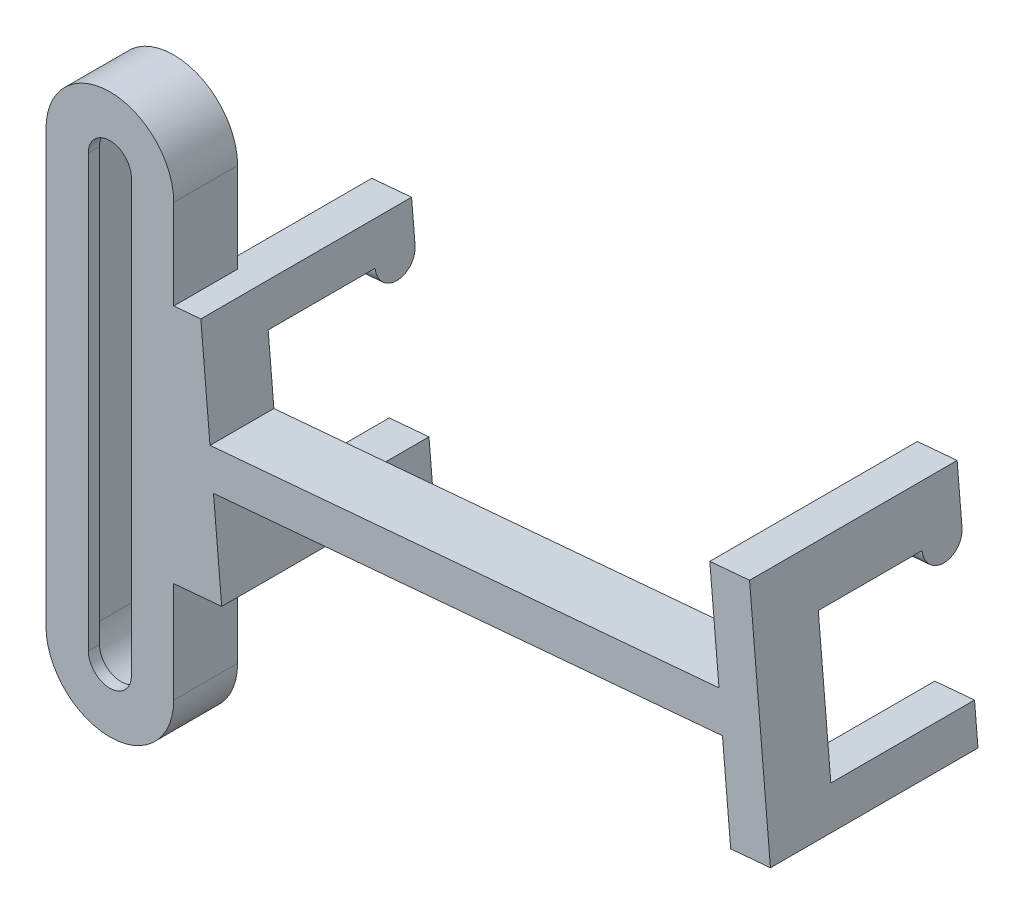
SolidWorks part; units mm, degrees
ref_plane "Front Plane" through (0, 0, 0) normal (0, 0, 1) x (1, 0, 0)
ref_plane "Top Plane" through (0, 0, 0) normal (0, 1, 0) x (1, 0, 0)
ref_plane "Right Plane" through (0, 0, 0) normal (1, 0, 0) x (0, 0, -1)
sketch "Sketch1" plane through (0, 0, 0) normal (0, 0, 1) x (1, 0, 0)
  line L1 (-10.16, -34.29) -> (10.16, -34.29)
  line L2 (-10.16, -34.29) -> (-10.16, 34.29)
  line L3 (-10.16, 34.29) -> (10.16, 34.29)
  line L4 (10.16, -34.29) -> (10.16, 34.29)
  line L5 (-10.16, -34.29) -> (10.16, 34.29) construction
  line L6 (-10.16, 34.29) -> (10.16, -34.29) construction
  circle A0 centre (0, 34.29) radius 10.16
  circle A1 centre (0, -34.29) radius 10.16
  point P0 (0, 0)
  dimension "D1" = 20.32
  dimension "D2" = 68.58
extrude "Boss-Extrude1" add sketch "Sketch1" along normal blind 10.16 contours A0 | L2 L1 L4 L3 | A1
sketch "Sketch2" plane through (0, 0, 10.16) normal (0, 0, 1) x (1, 0, 0)
  line L0 (6.604, 0) -> (10.16, 0) construction
  line L1 (-6.604, -34.29) -> (6.604, -34.29)
  line L2 (-6.604, -34.29) -> (-6.604, 34.29)
  line L3 (-6.604, 34.29) -> (6.604, 34.29)
  line L4 (6.604, -34.29) -> (6.604, 34.29)
  line L5 (-6.604, -34.29) -> (6.604, 34.29) construction
  line L6 (-6.604, 34.29) -> (6.604, -34.29) construction
  line L7 (10.16, -34.29) -> (10.16, 34.29) construction
  line L8 (0, 40.894) -> (0, 44.45) construction
  circle A0 centre (0, 34.29) radius 6.604
  circle A1 centre (0, -34.29) radius 6.604
  arc A2 (10.16, 34.29) -> (-10.16, 34.29) centre (0, 34.29) ccw construction
  point P0 (0, 0)
  dimension "D1" = 13.208
extrude "Cut-Extrude1" cut sketch "Sketch2" against normal through all contours A0 | L2 L1 L4 L3 | A1
sketch "Sketch3" plane through (0, 0, 0) normal (0, 0, -1) x (-1, 0, 0)
  line L0 (-10.16, -34.29) -> (-10.16, 34.29) construction
  line L1 (-9.6066, 3.1387) -> (-103.2289, 11.3296)
  line L2 (-9.6066, 3.1387) -> (-10.16, -3.1871)
  line L3 (-10.16, -3.1871) -> (-103.7824, 5.0038)
  line L4 (-103.2289, 11.3296) -> (-103.7824, 5.0038)
  line L5 (-103.5057, 8.1667) -> (-10.16, 0) construction
  dimension "D1" = 6.35
  dimension "D2" = 93.98
  dimension "D3" = 85
extrude "Boss-Extrude2" add sketch "Sketch3" against normal up to surface (10.16 mm away) up to face at (0, 0, 10.16)
ref_plane "Plane1" through (9.8061, 0.8579, 0) normal (-0.9962, -0.0872, 0) x (0, 0, 1)
sketch "Sketch4" plane through (-103.0822, 1291.1777, 0) normal (-0.9962, -0.0872, 0) x (0, 0, -1)
  line L1 (23.368, 1276.1986) -> (-10.16, 1276.1986)
  line L2 (23.368, 1276.1986) -> (23.368, 1314.2986)
  line L3 (23.368, 1314.2986) -> (-10.16, 1314.2986)
  line L4 (-10.16, 1276.1986) -> (-10.16, 1314.2986)
  line L5 (23.368, 1276.1986) -> (-10.16, 1314.2986) construction
  line L6 (23.368, 1314.2986) -> (-10.16, 1276.1986) construction
  line L7 (-10.16, 1292.9591) -> (-10.16, 1261.9746) construction
  line L8 (-10.16, 1328.5226) -> (-10.16, 1260.2036) construction
  point P0 (6.604, 1295.2486)
  dimension "D1" = 33.528
  dimension "D2" = 38.1
extrude "Boss-Extrude3" add sketch "Sketch4" against normal blind 6.35
sketch "Sketch5" plane through (16.1319, 1.4114, 0) normal (0.9962, 0.0872, 0) x (0, 0, 1)
  line L1 (-23.368, -12.7) -> (0, -12.7)
  line L2 (-23.368, -12.7) -> (-23.368, 12.7)
  line L3 (-23.368, 12.7) -> (0, 12.7)
  line L4 (0, -12.7) -> (0, 12.7)
  line L5 (-23.368, -12.7) -> (0, 12.7) construction
  line L6 (-23.368, 12.7) -> (0, -12.7) construction
  line L7 (0, 35.045) -> (0, 4.0605) construction
  line L8 (-23.368, -19.05) -> (-23.368, 19.05) construction
  point P0 (-11.684, 0)
  dimension "D2" = 25.4
extrude "Cut-Extrude2" cut sketch "Sketch5" against normal through all contours L3 L4 L1 L2
sketch "Sketch6" plane through (103.4285, 9.0488, 0) normal (0.9962, 0.0872, 0) x (0, 0, -1)
  line L8 (23.368, -19.05) -> (-10.16, -19.05) construction
  line L11 (-10.16, 19.05) -> (22.86, 19.05)
  line L13 (-10.16, 19.05) -> (-10.16, -19.05)
  line L14 (-10.16, -19.05) -> (22.86, -19.05)
  line L15 (22.86, 19.05) -> (22.86, -19.05)
  line L16 (0, 12.7) -> (0, 2.2895) construction
  dimension "D1" = 22.86
extrude "Boss-Extrude4" add sketch "Sketch6" against normal blind 6.35
sketch "Sketch7" plane through (9.8061, 0.8579, 0) normal (-0.9962, -0.0872, 0) x (0, 0, 1)
  line L0 (0, -4.0605) -> (0, -19.05)
  line L1 (0, -33.274) -> (0, 35.045) construction
  line L2 (-23.368, -19.05) -> (10.16, -19.05) construction
  line L3 (0, -19.05) -> (10.16, -19.05)
  line L4 (10.16, -33.274) -> (10.16, 35.045) construction
  line L5 (10.16, -19.05) -> (10.16, -4.0605)
  line L6 (10.16, -4.0605) -> (0, -4.0605)
extrude "Boss-Extrude5" add sketch "Sketch7" along normal up to next
sketch "Sketch8" plane through (97.1026, 8.4954, 0) normal (-0.9962, -0.0872, 0) x (0, 0, 1)
  line L0 (0, -33.274) -> (0, 35.045) construction
  line L1 (0, 10.16) -> (-22.86, 10.16)
  line L2 (0, 10.16) -> (0, -12.7)
  line L3 (0, -12.7) -> (-22.86, -12.7)
  line L4 (-22.86, 10.16) -> (-22.86, -12.7)
  line L5 (-22.86, -19.05) -> (-22.86, 19.05) construction
  line L7 (0, -12.7) -> (-23.368, -12.7) construction
  dimension "D1" = 22.86
extrude "Cut-Extrude3" cut sketch "Sketch8" against normal through all
sketch "Sketch9" plane through (9.8061, 0.8579, 0) normal (-0.9962, -0.0872, 0) x (0, 0, 1)
  line L1 (0, 12.7) -> (-23.368, 12.7) construction
  line L2 (-23.368, 19.05) -> (-23.368, 12.7) construction
  circle A0 centre (-20.193, 12.7) radius 3.175
  dimension "D1" = 6.35
extrude "Boss-Extrude6" add sketch "Sketch9" against normal up to surface (6.35 mm away) up to face at (17.1723, -10.48, -4.4027)
sketch "Sketch10" plane through (97.1026, 8.4954, 0) normal (-0.9962, -0.0872, 0) x (0, 0, 1)
  line L1 (0, 10.16) -> (-22.86, 10.16) construction
  line L2 (-22.86, 10.16) -> (-22.86, 19.05) construction
  circle A0 centre (-19.685, 10.16) radius 3.175
  dimension "D1" = 6.35
extrude "Boss-Extrude7" add sketch "Sketch10" against normal up to surface (6.35 mm away) up to face at (103.4838, 8.4162, -8.89)
sketch "Sketch13" plane through (16.1319, 1.4114, 0) normal (0.9962, 0.0872, 0) x (0, 0, -1)
  line L0 (-10.16, -4.0605) -> (0, -4.0605) construction
  circle A0 centre (-5.08, -4.0605) radius 2.286
  dimension "D1" = 4.572
extrude "Cut-Extrude4" cut sketch "Sketch13" against normal up to surface (81.28 mm away)
sketch "Sketch14" plane through (0, 0, 10.16) normal (0, 0, 1) x (1, 0, 0)
  line L0 (-3.429, 0) -> (3.429, 0) construction
  line L1 (0, 37.719) -> (0, 40.894) construction
  line L2 (3.429, 0) -> (6.604, 0) construction
  line L4 (-3.429, -34.29) -> (-3.429, 34.29)
  line L6 (3.429, -34.29) -> (3.429, 34.29)
  line L7 (6.604, -34.29) -> (6.604, 34.29) construction
  line L8 (-10.16, -34.29) -> (-10.16, 34.29) construction
  line L9 (-10.16, -34.29) -> (-10.16, 34.29)
  line L10 (10.16, 34.29) -> (10.16, -34.29)
  arc A0 (6.604, 34.29) -> (-6.604, 34.29) centre (0, 34.29) ccw construction
  arc A1 (3.429, 34.29) -> (-3.429, 34.29) centre (0, 34.29) ccw
  arc A2 (-3.429, -34.29) -> (3.429, -34.29) centre (0, -34.29) ccw
  arc A3 (-10.16, -34.29) -> (10.16, -34.29) centre (0, -34.29) ccw construction
  arc A4 (10.16, 34.29) -> (-10.16, 34.29) centre (0, 34.29) ccw construction
  arc A5 (-10.16, -34.29) -> (10.16, -34.29) centre (0, -34.29) ccw
  arc A6 (10.16, 34.29) -> (-10.16, 34.29) centre (0, 34.29) ccw
  point P1 (0, 0)
  point P6 (0, 0)
  dimension "D1" = 6.858
extrude "Boss-Extrude8" add sketch "Sketch14" against normal blind 1.778
